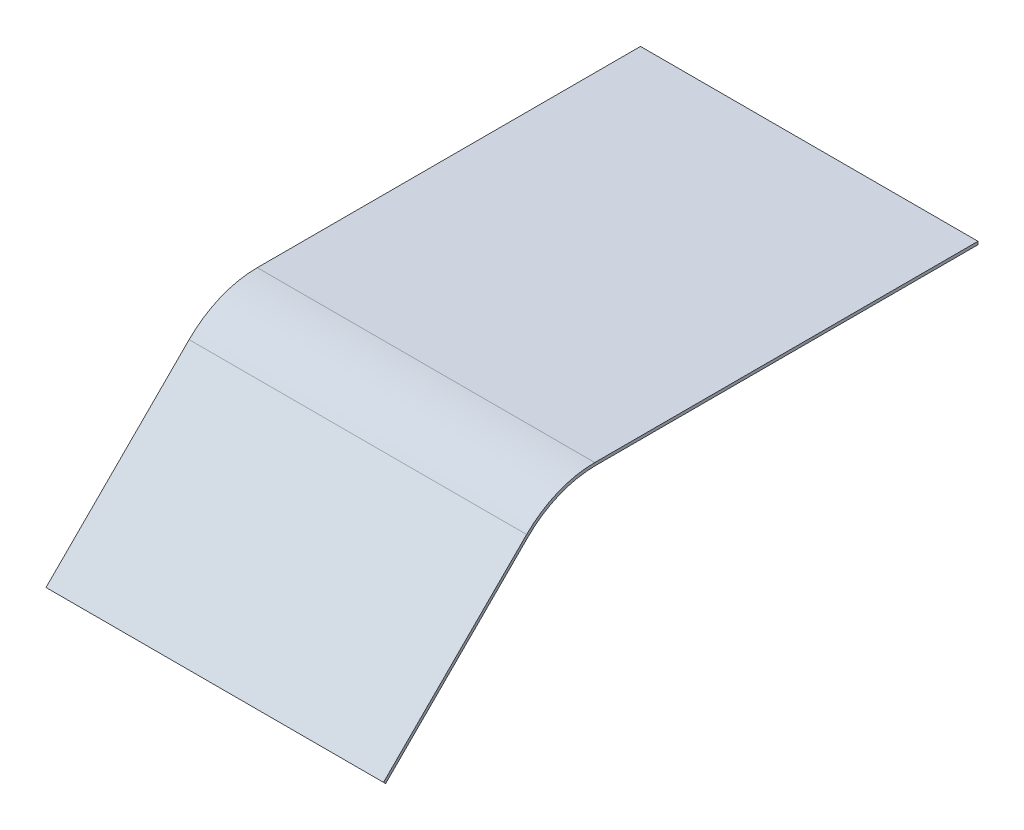
SolidWorks part; units mm, degrees
ref_plane "Front Plane" through (0, 0, 0) normal (0, 0, 1) x (1, 0, 0)
ref_plane "Top Plane" through (0, 0, 0) normal (0, 1, 0) x (1, 0, 0)
ref_plane "Right Plane" through (0, 0, 0) normal (1, 0, 0) x (0, 0, -1)
sketch "Sketch1" plane through (0, 0, 0) normal (1, 0, 0) x (0, 0, -1)
  line L0 (21.042, 0) -> (222.25, 0)
  line L1 (222.25, 0) -> (222.25, 1.5875)
  line L2 (222.25, 1.5875) -> (20.3845, 1.5875)
  line L3 (-15.5365, -13.2915) -> (-90.9251, -88.68)
  line L4 (-90.9251, -88.68) -> (-89.8026, -89.8026)
  line L5 (-89.8026, -89.8026) -> (-14.879, -14.879)
  arc A0 (20.3845, 1.5875) -> (-15.5365, -13.2915) centre (20.3845, -49.2125) ccw
  arc A1 (21.042, 0) -> (-14.879, -14.879) centre (21.042, -50.8) ccw
  point P11 (0, 0)
  point P12 (-63.5469, -42.589)
  dimension "D5" = 50.8
  dimension "D1" = 135
  dimension "D2" = 127
  dimension "D3" = 222.25
  dimension "D4" = 1.5875
extrude "Boss-Extrude1" add sketch "Sketch1" along normal blind 177.8
